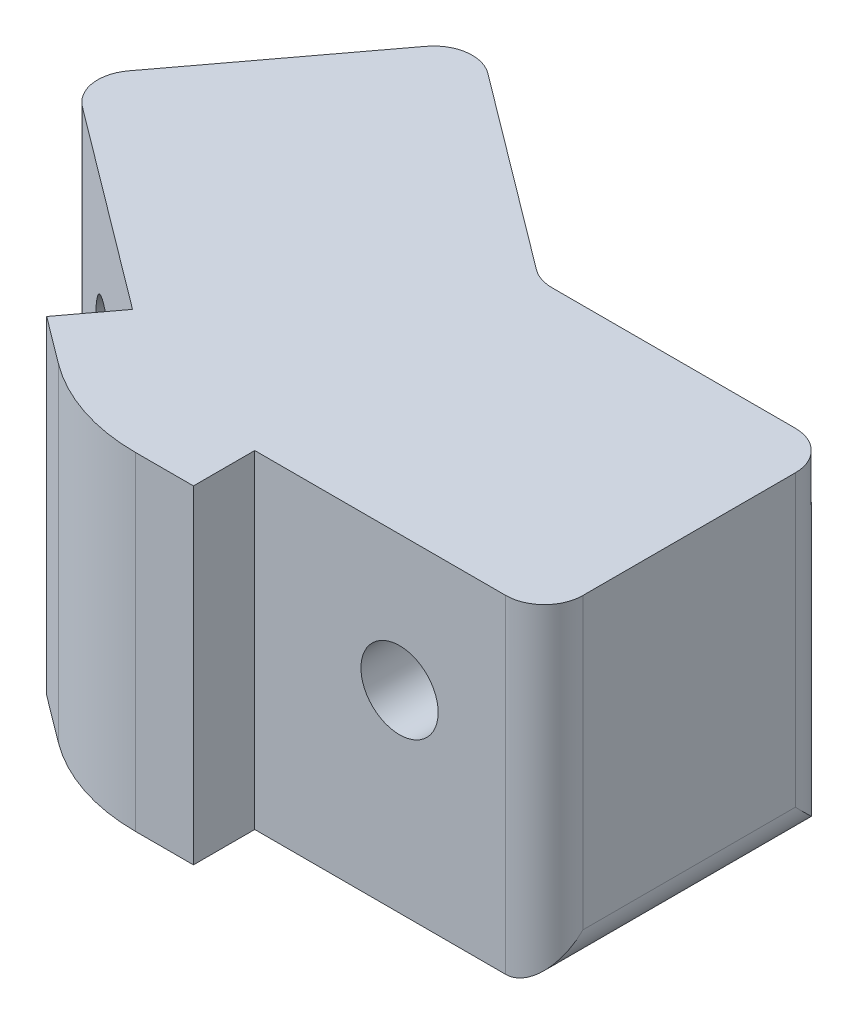
SolidWorks part; units mm, degrees
ref_plane "Front Plane" through (0, 0, 0) normal (0, 0, 1) x (1, 0, 0)
ref_plane "Top Plane" through (0, 0, 0) normal (0, 1, 0) x (1, 0, 0)
ref_plane "Right Plane" through (0, 0, 0) normal (1, 0, 0) x (0, 0, -1)
sketch "Sketch1" plane through (0, 0, 0) normal (0, 1, 0) x (1, 0, 0)
  line L0 (0, -10) -> (0, -6.825) construction
  line L2 (18, -6.825) -> (18, 54) construction
  line L3 (-6, -8) -> (-4.095, -5.46) construction
  line L5 (-18.495, 5.34) -> (18, 54) construction
  line L6 (-4.095, -5.46) -> (0, 0) construction
  line L8 (0, 0) -> (0, -6.825) construction
  line L9 (-3.1623, -9.4868) -> (0, 0) construction
  line L10 (0, 0) -> (18, 54) construction
  line L11 (-18.495, 5.34) -> (-9.495, 17.34)
  line L12 (-9.495, 17.34) -> (2.725, 8.175)
  line L13 (18, -6.825) -> (18, 8.175)
  line L14 (18, 8.175) -> (2.725, 8.175)
  line L15 (-6, -8) -> (-8.4, -6.2)
  line L16 (-8.4, -6.2) -> (-6.495, -3.66)
  line L17 (0, -10) -> (3, -10)
  line L18 (3, -10) -> (3, -6.825)
  line L19 (-18.495, 5.34) -> (-6.495, -3.66)
  line L20 (-6.495, -3.66) -> (-4.095, -5.46) construction
  line L21 (0, -6.825) -> (3, -6.825) construction
  line L22 (3, -6.825) -> (18, -6.825)
  line L23 (-6, -8) -> (-79.3333, 47) construction
  arc A0 (0, -10) -> (-6, -8) centre (0, 0) cw
  dimension "D1" = 10
  dimension "D2" = 3.175
  dimension "D4" = 15
  dimension "D5" = 15
  dimension "D6" = 3
extrude "Boss-Extrude1" add sketch "Sketch1" along normal blind 70
sketch "Sketch2" plane through (0, 0, 6.825) normal (0, 0, 1) x (1, 0, 0)
  line L0 (10.5, 0) -> (10.5, 70) construction
  line L1 (3, 0) -> (18, 0) construction
  line L2 (3, 70) -> (18, 70) construction
  circle A0 centre (10.5, 10) radius 2
  circle A1 centre (10.5, 60) radius 2
  dimension "D1" = 4
  dimension "D2" = 10
  dimension "D3" = 10
extrude "Cut-Extrude1" cut sketch "Sketch2" against normal up to surface (15 mm away) up to face at (10.3625, 35, -8.175)
sketch "Sketch3" plane through (-4.095, 0, 5.46) normal (-0.6, 0, 0.8) x (0.8, 0, 0.6)
  line L0 (-10.5, 0) -> (-10.5, 70) construction
  line L1 (-18, 0) -> (-3, 0) construction
  line L2 (-18, 70) -> (-3, 70) construction
  circle A0 centre (-10.5, 10) radius 2
  circle A1 centre (-10.5, 60) radius 2
  dimension "D1" = 4
  dimension "D3" = 10
  dimension "D2" = 10
extrude "Cut-Extrude2" cut sketch "Sketch3" against normal up to surface (15 mm away) up to face at (-3.385, 35, -12.7575)
sketch "Sketch4" plane through (4.905, 0, -6.54) normal (0.6, 0, -0.8) x (-0.8, 0, -0.6)
  line L0 (6.2813, 12.4357) -> (10.5, 14.8714)
  line L1 (10.5, 55.1286) -> (14.7188, 57.5643)
  line L2 (14.7188, 57.5643) -> (14.7188, 62.4357)
  line L3 (14.7188, 62.4357) -> (10.5, 64.8714)
  line L4 (10.5, 64.8714) -> (6.2813, 62.4357)
  line L5 (6.2813, 62.4357) -> (6.2813, 57.5643)
  line L6 (6.2813, 57.5643) -> (10.5, 55.1286)
  line L7 (10.5, 14.8714) -> (6.2813, 12.4357) construction
  line L8 (6.2813, 12.4357) -> (6.2813, 7.5643) construction
  line L9 (6.2813, 7.5643) -> (10.5, 5.1286) construction
  line L10 (10.5, 5.1286) -> (14.7188, 7.5643) construction
  line L11 (14.7188, 7.5643) -> (14.7188, 12.4357) construction
  line L12 (14.7188, 12.4357) -> (10.5, 14.8714) construction
  line L13 (10.5, 14.8714) -> (14.7188, 12.4357)
  line L14 (14.7188, 12.4357) -> (14.7188, 0)
  line L15 (2.725, 0) -> (18, 0) construction
  line L16 (14.7188, 0) -> (6.2813, 0)
  line L17 (6.2813, 0) -> (6.2813, 12.4357)
  circle A0 centre (10.5, 60) radius 4.2188 construction
  circle A1 centre (10.5, 10) radius 4.2188 construction
  dimension "D1" = 8.4375
extrude "Cut-Extrude3" cut sketch "Sketch4" against normal blind 3 from offset 3 offset against normal yes
sketch "Sketch5" plane through (0, 0, -8.175) normal (0, 0, -1) x (-1, 0, 0)
  line L0 (-14.7188, 12.4357) -> (-10.5, 14.8714)
  line L1 (-10.5, 55.1286) -> (-6.2813, 57.5643)
  line L2 (-6.2813, 57.5643) -> (-6.2813, 62.4357)
  line L3 (-6.2813, 62.4357) -> (-10.5, 64.8714)
  line L4 (-10.5, 64.8714) -> (-14.7188, 62.4357)
  line L5 (-14.7188, 62.4357) -> (-14.7188, 57.5643)
  line L6 (-14.7188, 57.5643) -> (-10.5, 55.1286)
  line L7 (-10.5, 5.1286) -> (-6.2813, 7.5643) construction
  line L8 (-6.2813, 7.5643) -> (-6.2813, 12.4357) construction
  line L9 (-6.2813, 12.4357) -> (-10.5, 14.8714) construction
  line L10 (-10.5, 14.8714) -> (-14.7188, 12.4357) construction
  line L11 (-14.7188, 12.4357) -> (-14.7188, 7.5643) construction
  line L12 (-14.7188, 7.5643) -> (-10.5, 5.1286) construction
  line L13 (-10.5, 14.8714) -> (-6.2813, 12.4357)
  line L14 (-6.2813, 12.4357) -> (-6.2813, 0)
  line L15 (-18, 0) -> (-2.725, 0) construction
  line L16 (-6.2813, 0) -> (-14.7188, 0)
  line L17 (-14.7188, 0) -> (-14.7188, 12.4357)
  circle A0 centre (-10.5, 60) radius 4.2188 construction
  circle A1 centre (-10.5, 10) radius 4.2188 construction
  dimension "D1" = 8.4375
extrude "Cut-Extrude4" cut sketch "Sketch5" against normal blind 3 from offset 3 offset against normal yes
ref_plane "Plane1" through (4.2525, 0, -12.7575) normal (0.3162, 0, -0.9487) x (-0.9487, 0, -0.3162)
fillet "Fillet1" radius 2 7 edges at (2.725, 35, -8.175) (18, 35, 6.825) (18, 35, -8.175) (-9.495, 35, -17.34) (-18.495, 35, -5.34) (18, 0, -0.675) (-13.995, 0, -11.34)
sketch "Sketch8" plane through (0, 70, 0) normal (0, 1, 0) x (1, 0, 0)
  line L1 (22.6827, -12.8611) -> (-23.2713, -12.8611)
  line L2 (22.6827, -12.8611) -> (22.6827, 19.0631)
  line L3 (22.6827, 19.0631) -> (-23.2713, 19.0631)
  line L4 (-23.2713, -12.8611) -> (-23.2713, 19.0631)
extrude "Cut-Extrude6" cut sketch "Sketch8" against normal blind 53
sketch "Sketch9" plane through (4.905, 0, -6.54) normal (0.6, 0, -0.8) x (-0.8, 0, -0.6)
  line L0 (12.5, 10) -> (12.5, 0)
  line L1 (3.3917, 0) -> (16, 0) construction
  line L2 (12.5, 0) -> (8.5, 0)
  line L3 (8.5, 0) -> (8.5, 10)
  arc A0 (8.5, 10) -> (12.5, 10) centre (10.5, 10) ccw
  circle A1 centre (10.5, 10) radius 2 construction
extrude "Cut-Extrude7" cut sketch "Sketch9" against normal blind 3
sketch "Sketch10" plane through (0, 0, -8.175) normal (0, 0, -1) x (-1, 0, 0)
  line L0 (-8.5, 10) -> (-8.5, 0)
  line L1 (-16, 0) -> (-3.3917, 0) construction
  line L2 (-8.5, 0) -> (-12.5, 0)
  line L3 (-12.5, 0) -> (-12.5, 10)
  arc A0 (-12.5, 10) -> (-8.5, 10) centre (-10.5, 10) ccw
  circle A1 centre (-10.5, 10) radius 2 construction
extrude "Cut-Extrude8" cut sketch "Sketch10" against normal blind 3
sketch "Sketch11" plane through (0, 0, 0) normal (0, -1, 0) x (1, 0, 0)
  line L0 (-3.1623, 9.4868) -> (2.7592, -8.2776) construction
  line L1 (0.3333, -1) -> (-13.8, -11.6) construction
  line L2 (-10.695, -15.74) -> (-17.295, -6.94) construction
  line L3 (-16.895, -4.14) -> (-6.495, 3.66) construction
  line L4 (-8.4, 6.2) -> (-6, 8) construction
  arc A0 (0, 10) -> (-6, 8) centre (0, 0) ccw construction
  arc A1 (3.3917, -8.175) -> (2.1917, -8.575) centre (3.3917, -10.175) ccw construction
  circle A2 centre (0.3333, -1) radius 2.3876
  dimension "D2" = 4.7752
  dimension "D1" = 11
extrude "Cut-Extrude9" cut sketch "Sketch11" against normal blind 6.35 draft 8 contours A2
sketch "Sketch12" plane through (0, 6.35, 0) normal (0, -1, 0) x (1, 0, 0)
  circle A0 centre (0.3333, -1) radius 1.4952
  circle A1 centre (0.3333, -1) radius 1.4952 construction
extrude "Cut-Extrude10" cut sketch "Sketch12" against normal blind 5
fillet "Fillet2" radius 1 4 edges at (12.5, 0, -6.675) (8.5, 0, -6.675) (-5.995, 0, -12.84) (-2.795, 0, -10.44)
